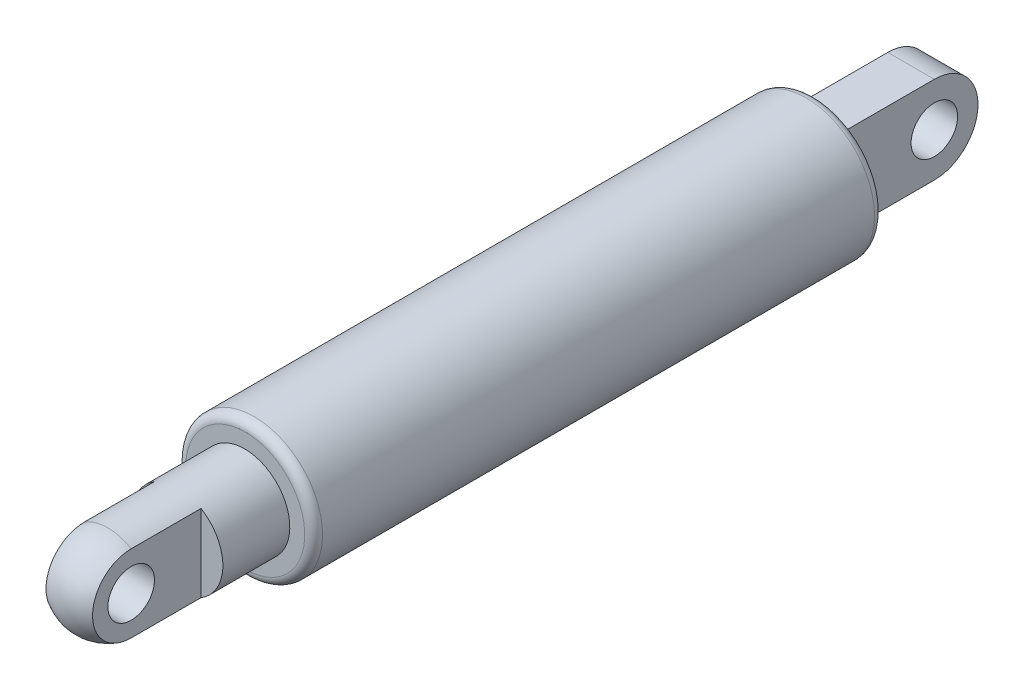
SolidWorks part; units mm, degrees
ref_plane "Front" through (0, 0, 0) normal (0, 0, 1) x (1, 0, 0)
ref_plane "Top" through (0, 0, 0) normal (0, 1, 0) x (1, 0, 0)
ref_plane "Right" through (0, 0, 0) normal (1, 0, 0) x (0, 0, -1)
sketch "Sketch1" plane through (0, 0, 0) normal (1, 0, 0) x (0, 0, -1)
  line L0 (-45.085, 0) -> (45.085, 0) construction
  line L1 (-45.085, 0) -> (-45.085, -0.254) construction
  line L2 (-25.019, 0) -> (-25.019, -0.254) construction
  line L3 (45.085, -0.254) -> (45.085, 0) construction
  line L4 (36.703, 0) -> (36.703, 5.969)
  line L5 (-13.0302, 2.0828) -> (-13.0302, 5.969)
  line L6 (-33.147, 0) -> (-33.147, 2.032) construction
  line L7 (-33.147, 2.032) -> (-13.0302, 2.032) construction
  line L8 (-13.0302, 5.969) -> (36.703, 5.969)
  line L11 (19.2786, 0) -> (36.703, 0)
  line L12 (-13.0302, 2.0828) -> (7.0866, 2.0828)
  line L13 (7.0866, 2.0828) -> (7.0866, 0) construction
  line L14 (7.0866, 2.0828) -> (19.2786, 2.0828)
  line L15 (19.2786, 2.0828) -> (19.2786, 0)
  line L16 (-13.0302, 2.0828) -> (-13.0302, 2.032) construction
  dimension "B Compressed Length" = 70.104
  dimension "C Stroke" = 20.066
  dimension "D4" = 8.382
  dimension "D5" = 11.938
  dimension "D6" = 11.9888
  dimension "E Cylinder Dia" = 11.938
  dimension "D Rod Dia" = 4.064
  dimension "D7" = 0.0508
  dimension "D8" = 12.192
  dimension "D9" = 3.8862
  dimension "A Ext Length" = 90.17
  dimension "D1" = 0.254
revolve "Revolve1" add sketch "Sketch1" angle 360 about L0
fillet "Fillet2" radius 0.7772 2 edges at (5.969, 0, -36.703) (5.969, 0, 13.0302)
sketch "Sketch2" plane through (0, 0, 0) normal (1, 0, 0) x (0, 0, -1)
  line L0 (36.703, 3.81) -> (45.085, 3.81)
  line L2 (36.703, -3.81) -> (36.703, 3.81)
  line L5 (36.703, 0) -> (36.703, 5.969) construction
  line L7 (36.703, -3.81) -> (45.085, -3.81)
  arc A0 (45.085, 3.81) -> (45.085, -3.81) centre (45.085, 0) cw
  circle A3 centre (45.085, 0) radius 2.032
  dimension "D4" = 4.064
  dimension "D1" = 7.62
extrude "Extrude2" add sketch "Sketch2" along normal mid plane 4.064
sketch "Sketch9" plane through (0, 0, 0) normal (1, 0, 0) x (0, 0, -1)
  line L0 (-33.147, 0) -> (-33.147, 2.032) construction
  line L2 (-33.147, 0) -> (-33.147, 2.032)
  line L3 (-33.147, 2.032) -> (-0.8382, 2.032)
  line L4 (-0.8382, 2.032) -> (-0.8382, 0)
  line L5 (-0.8382, 0) -> (-33.147, 0)
  line L6 (-33.147, 0) -> (-45.085, 0) construction
  line L8 (-0.8382, 1.016) -> (-13.0302, 1.016) construction
  line L9 (-13.0302, 1.016) -> (-13.0302, 2.032) construction
  line L10 (7.0866, 2.0828) -> (19.2786, 2.0828) construction
revolve "Revolve5" add sketch "Sketch9" angle 360 about L6
sketch "Sketch11" plane through (0, 0, 0) normal (1, 0, 0) x (0, 0, -1)
  line L0 (-33.147, 0) -> (-33.147, 3.937)
  line L1 (-33.147, 3.937) -> (-45.085, 3.937)
  line L2 (-49.022, 0) -> (-33.147, 0)
  line L3 (-49.022, 0) -> (-52.959, 0) construction
  line L4 (-45.085, 0) -> (45.085, 0) construction
  arc A0 (-45.085, 3.937) -> (-49.022, 0) centre (-45.085, 0) ccw
  circle A1 centre (-45.085, 0) radius 2.032 construction
  dimension "D2" = 4.064
  dimension "D1" = 7.874
revolve "Revolve6" add sketch "Sketch11" angle 360 about L3
sketch "Sketch12" plane through (0, 0, 0) normal (1, 0, 0) x (0, 0, -1)
  circle A0 centre (-45.085, 0) radius 2.032 construction
  circle A1 centre (-45.085, 0) radius 2.032
extrude "Cut-Extrude1" cut sketch "Sketch12" against normal through all and the other way through all
ref_plane "Plane1" through (0, 0, 45.085) normal (0, 0, 1) x (1, 0, 0)
sketch "Sketch13" plane through (0, 0, 45.085) normal (0, 0, 1) x (1, 0, 0)
  line L0 (-2.032, -3.937) -> (2.032, 3.937) construction
  line L1 (-2.032, 3.937) -> (2.032, 3.937)
  line L2 (-2.032, 3.937) -> (-2.032, -3.937)
  line L3 (-2.032, -3.937) -> (2.032, -3.937)
  line L4 (2.032, 3.937) -> (2.032, -3.937)
  dimension "D1" = 4.064
extrude "Cut-Extrude2" cut sketch "Sketch13" against normal blind 6.096 and the other way through all flip side to cut
pattern_linear "LPattern1" count 2 spacing 20.066 along (0, 0, -1) of bodies 137
sketch "Sketch10" plane through (0, 0, 0) normal (1, 0, 0) x (0, 0, -1)
  line L0 (-33.147, 2.032) -> (-13.0302, 2.032) construction
  line L2 (-33.147, -2.032) -> (-0.8382, -2.032) construction
  arc A0 (-28.3911, 2.032) -> (-28.3911, -2.032) centre (-25.019, 0) ccw
  arc A1 (-25.019, 3.937) -> (-25.019, -3.937) centre (-25.019, 0) ccw construction
sketch "Sketch14" plane through (0, 0, 0) normal (1, 0, 0) x (0, 0, -1)
  line L0 (-33.147, 3.937) -> (-33.147, 2.032)
  line L1 (-33.147, -2.032) -> (-33.147, -3.937)
  line L2 (-0.8382, -2.032) -> (-33.147, -2.032)
  line L3 (-33.147, 2.032) -> (-0.8382, 2.032)
  line L4 (-0.8382, 2.032) -> (-0.8382, -2.032)
  line L5 (-33.147, -3.937) -> (-45.085, -3.937)
  line L6 (-45.085, 3.937) -> (-33.147, 3.937)
  line L7 (-45.085, 3.937) -> (-33.147, 3.937)
  line L8 (-33.147, -3.937) -> (-45.085, -3.937)
  line L9 (-0.8382, 2.032) -> (-0.8382, -2.032)
  line L10 (-33.147, 2.032) -> (-0.8382, 2.032)
  line L11 (-0.8382, -2.032) -> (-33.147, -2.032)
  line L12 (-33.147, -2.032) -> (-33.147, -3.937)
  line L13 (-33.147, 3.937) -> (-33.147, 2.032)
  circle A0 centre (-45.085, 0) radius 2.032
  arc A1 (-45.085, 3.937) -> (-45.085, -3.937) centre (-45.085, 0) ccw
  arc A2 (-45.085, 3.937) -> (-45.085, -3.937) centre (-45.085, 0) ccw
  circle A5 centre (-45.085, 0) radius 2.032
  point P12 (-49.022, 0)
delete or keep bodies "Body-Delete/Keep 1" type delete bodies bodies 137
equation "\"D1@Fillet2\"=\"D9@Sketch1\"/5"
equation "\"D3@LPattern1\"=\"C Stroke@Sketch1\""
